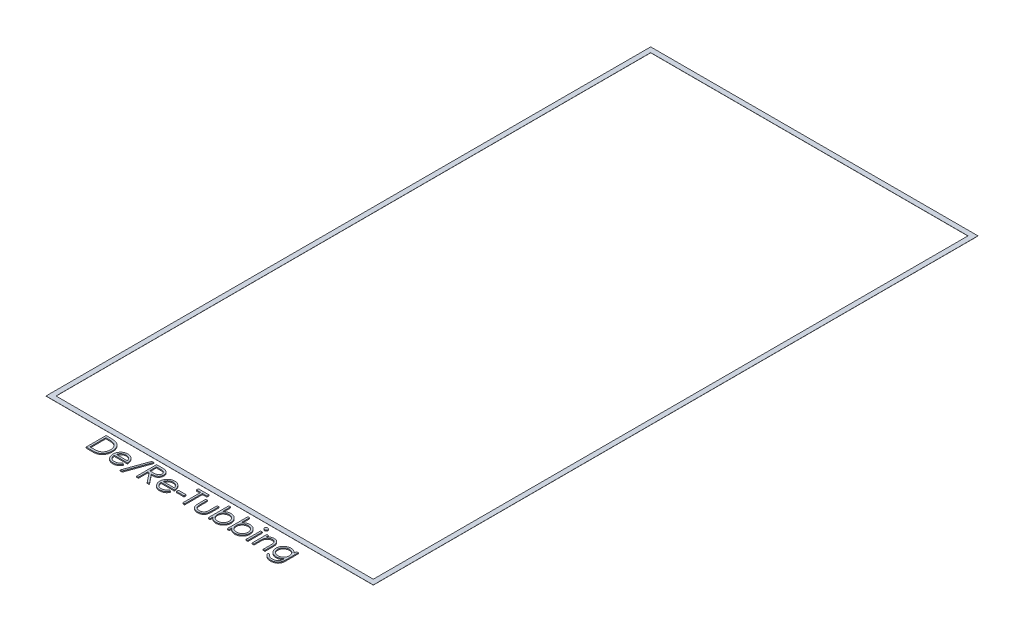
SolidWorks part; units mm, degrees
ref_plane "Front Plane" through (0, 0, 0) normal (0, 0, 1) x (1, 0, 0)
ref_plane "Top Plane" through (0, 0, 0) normal (0, 1, 0) x (1, 0, 0)
ref_plane "Right Plane" through (0, 0, 0) normal (1, 0, 0) x (0, 0, -1)
sketch "Sketch1" plane through (0, 0, 0) normal (0, 1, 0) x (1, 0, 0)
  line L0 (-322.3345, 600.1655) -> (-322.3345, -599.8345) construction
  line L1 (-322.3345, -599.8345) -> (322.6655, -599.8345) construction
  line L2 (322.6655, -599.8345) -> (322.6655, 600.1655) construction
  line L3 (322.6655, 600.1655) -> (-322.3345, 600.1655) construction
  line L4 (-327.3345, 605.1655) -> (-327.3345, -604.8345)
  line L5 (-327.3345, -604.8345) -> (327.6655, -604.8345)
  line L6 (327.6655, -604.8345) -> (327.6655, 605.1655)
  line L7 (327.6655, 605.1655) -> (-327.3345, 605.1655)
  line L8 (-317.3345, 595.1655) -> (-317.3345, -594.8345)
  line L9 (-317.3345, -594.8345) -> (317.6655, -594.8345)
  line L10 (317.6655, -594.8345) -> (317.6655, 595.1655)
  line L11 (317.6655, 595.1655) -> (-317.3345, 595.1655)
  dimension "D1" = 645
  dimension "D2" = 5
  dimension "D3" = 5
extrude "Boss-Extrude1" add sketch "Sketch1" along normal blind 0.3
sketch "Sketch2" plane through (0, 0, 0) normal (0, 1, 0) x (1, 0, 0)
  line L0 (-317.3345, -654.8345) -> (317.6655, -654.8345) construction
  line L1 (-317.3345, 595.1655) -> (-317.3345, -594.8345) construction
  line L2 (317.6655, -594.8345) -> (317.6655, 595.1655) construction
  line L4 (-327.3345, -604.8345) -> (327.6655, -604.8345) construction
  text T0 "De/Re-Tubbing" font "Century Gothic" height 40
  dimension "D1" = 50
extrude "Boss-Extrude3" add sketch "Sketch2" along normal blind 2
